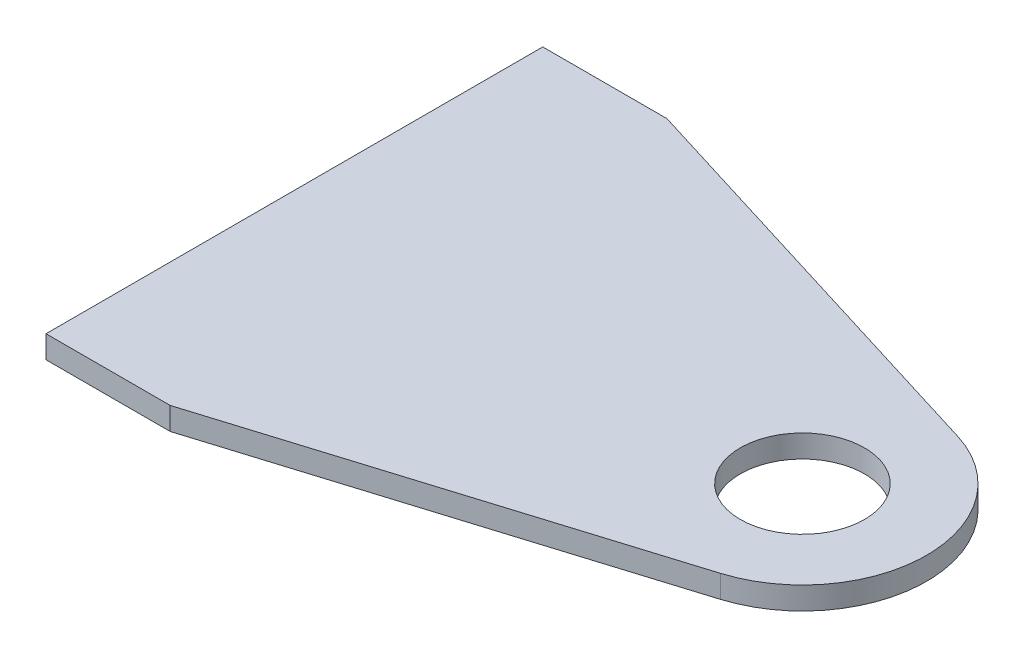
SolidWorks part; units mm, degrees
ref_plane "Front Plane" through (0, 0, 0) normal (0, 0, 1) x (1, 0, 0)
ref_plane "Top Plane" through (0, 0, 0) normal (0, 1, 0) x (1, 0, 0)
ref_plane "Right Plane" through (0, 0, 0) normal (1, 0, 0) x (0, 0, -1)
sketch "sketch_w_dimensions" plane through (0, 0, 0) normal (0, 1, 0) x (1, 0, 0)
  line L0 (-225, 110) -> (-225, -110)
  line L1 (-225, -110) -> (-170, -110)
  line L2 (-225, 110) -> (-170, 110)
  line L3 (-170, 110) -> (16.2128, 52.5561)
  line L4 (-170, -110) -> (16.2128, -52.5561)
  circle A0 centre (0, 0) radius 27.5
  arc A2 (16.2128, -52.5561) -> (16.2128, 52.5561) centre (0, 0) ccw
  point P7 (0, 0)
  point P8 (0, 0)
  dimension "D1" = 55
  dimension "D5" = 55
  dimension "D6" = 110
  dimension "D2" = 110
  dimension "D3" = 220
  dimension "D4" = 55
  dimension "D7" = 225
extrude "extrude_10mm" add sketch "sketch_w_dimensions" along normal blind 10
